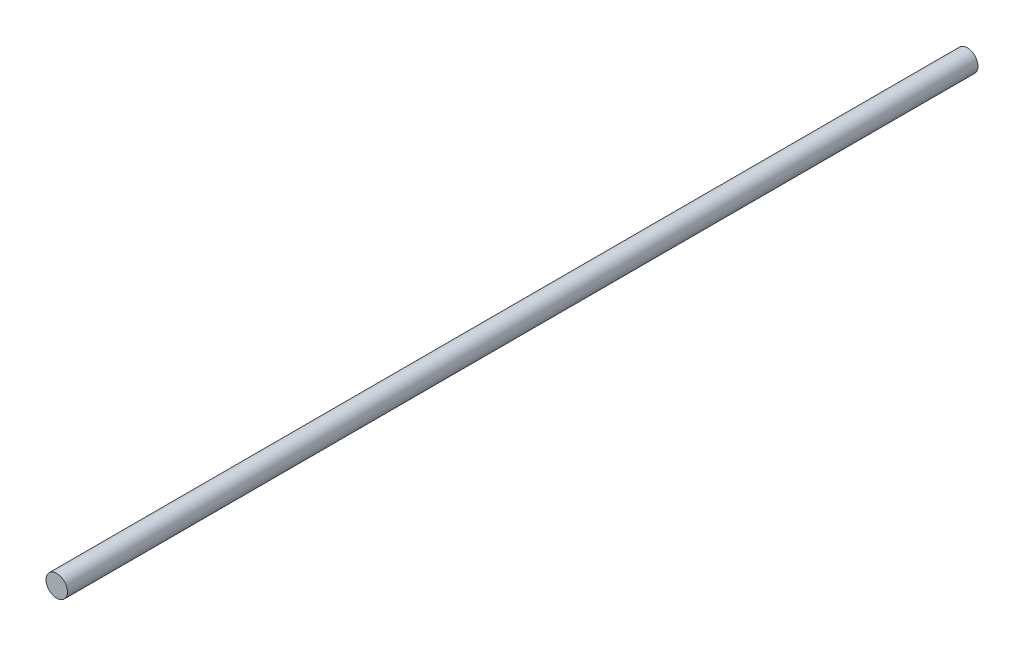
SolidWorks part; units mm, degrees
ref_plane "Front Plane" through (0, 0, 0) normal (0, 0, 1) x (1, 0, 0)
ref_plane "Top Plane" through (0, 0, 0) normal (0, 1, 0) x (1, 0, 0)
ref_plane "Right Plane" through (0, 0, 0) normal (1, 0, 0) x (0, 0, -1)
sketch "Sketch1" plane through (0, 0, 0) normal (0, 0, 1) x (1, 0, 0)
  circle A0 centre (0, 0) radius 3.175
  dimension "D1" = 6.35
extrude "Boss-Extrude1" add sketch "Sketch1" along normal blind 269
